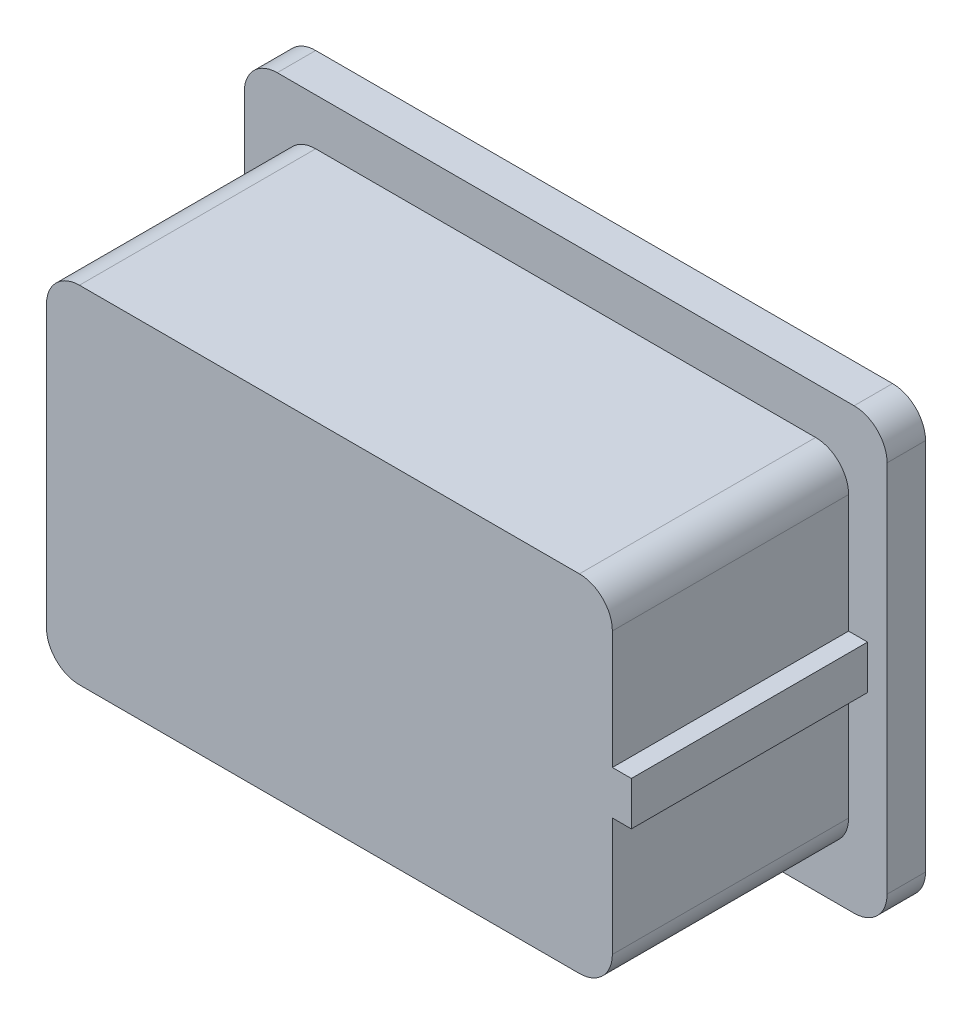
SolidWorks part; units mm, degrees
ref_plane "Front Plane" through (0, 0, 0) normal (0, 0, 1) x (1, 0, 0)
ref_plane "Top Plane" through (0, 0, 0) normal (0, 1, 0) x (1, 0, 0)
ref_plane "Right Plane" through (0, 0, 0) normal (1, 0, 0) x (0, 0, -1)
sketch "草图1" plane through (0, 0, 0) normal (0, 0, 1) x (1, 0, 0)
  line L1 (-29.25, 20) -> (29.25, 20)
  line L2 (-29.25, 20) -> (-29.25, -20)
  line L3 (-29.25, -20) -> (29.25, -20)
  line L4 (29.25, 20) -> (29.25, -20)
  line L5 (-29.25, 20) -> (29.25, -20) construction
  line L6 (-29.25, -20) -> (29.25, 20) construction
  point P1 (0, 0)
  dimension "D1" = 58.5
  dimension "D2" = 40
extrude "凸台-拉伸1" add sketch "草图1" along normal blind 25
sketch "草图2" plane through (0, 0, 25) normal (0, 0, 1) x (1, 0, 0)
  line L1 (-25.75, -15.75) -> (25.75, -15.75)
  line L2 (-25.75, -15.75) -> (-25.75, 15.75)
  line L3 (-25.75, 15.75) -> (25.75, 15.75)
  line L4 (25.75, -15.75) -> (25.75, 15.75)
  line L5 (-25.75, -15.75) -> (25.75, 15.75) construction
  line L6 (-25.75, 15.75) -> (25.75, -15.75) construction
  point P0 (0, 0)
  dimension "D1" = 51.5
  dimension "D2" = 31.5
extrude "切除-拉伸4" cut sketch "草图2" against normal blind 21.5 flip side to cut
sketch "草图3" plane through (0, 0, 25) normal (0, 0, 1) x (1, 0, 0)
  line L0 (25.75, -15.75) -> (25.75, 15.75) construction
  line L1 (24.0211, 1.9887) -> (27.4789, 1.9887)
  line L2 (24.0211, 1.9887) -> (24.0211, -1.9887)
  line L3 (24.0211, -1.9887) -> (27.4789, -1.9887)
  line L4 (27.4789, 1.9887) -> (27.4789, -1.9887)
  line L5 (24.0211, 1.9887) -> (27.4789, -1.9887) construction
  line L6 (24.0211, -1.9887) -> (27.4789, 1.9887) construction
  point P0 (25.75, 0)
extrude "凸台-拉伸2" add sketch "草图3" against normal up to next
fillet "圆角1" radius 3 2 edges at (25.75, 15.75, 14.25) (25.75, -15.75, 14.25)
fillet "圆角2" radius 3 2 edges at (-25.75, 15.75, 14.25) (-25.75, -15.75, 14.25)
fillet "圆角3" radius 3 4 edges at (29.25, 20, 1.75) (29.25, -20, 1.75) (-29.25, 20, 1.75) (-29.25, -20, 1.75)
